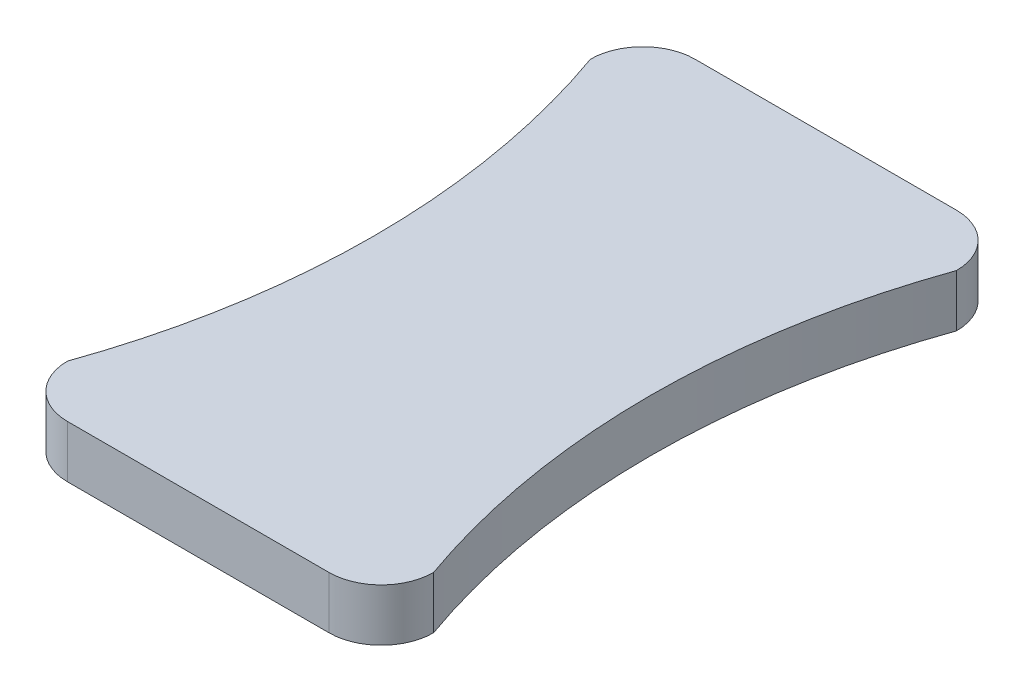
SolidWorks part; units mm, degrees
ref_plane "Front Plane" through (0, 0, 0) normal (0, 0, 1) x (1, 0, 0)
ref_plane "Top Plane" through (0, 0, 0) normal (0, 1, 0) x (1, 0, 0)
ref_plane "Right Plane" through (0, 0, 0) normal (1, 0, 0) x (0, 0, -1)
sketch "Sketch2" plane through (0, 0, 0) normal (0, 1, 0) x (1, 0, 0)
  line L1 (-25, 60) -> (25, 60)
  line L2 (-35, 50) -> (-35, -50) construction
  line L3 (-25, -60) -> (25, -60)
  line L4 (35, 50) -> (35, -50) construction
  line L5 (-35, 60) -> (35, -60) construction
  line L6 (-35, -60) -> (35, 60) construction
  arc A0 (-25, -60) -> (-35, -50) centre (-25, -50) cw
  arc A1 (25, -60) -> (35, -50) centre (25, -50) ccw
  arc A2 (35, 50) -> (25, 60) centre (25, 50) ccw
  arc A3 (-25, 60) -> (-35, 50) centre (-25, 50) ccw
  arc A4 (-35, 50) -> (-35, -50) centre (-176.4214, 0) cw
  arc A5 (35, 50) -> (35, -50) centre (176.4214, 0) ccw
  point P0 (0, 0)
  point P5 (-35, 0)
  point P7 (35, 0)
  point P8 (0, 60)
  point P9 (0, -60)
  point P23 (-26.4214, 0)
  point P25 (0, 0)
  point P26 (26.4214, 0)
  dimension "D3" = 10
  dimension "D4" = 150
  dimension "D1" = 70
  dimension "D2" = 120
  dimension "D5" = 150
extrude "Boss-Extrude1" add sketch "Sketch2" along normal blind 10
